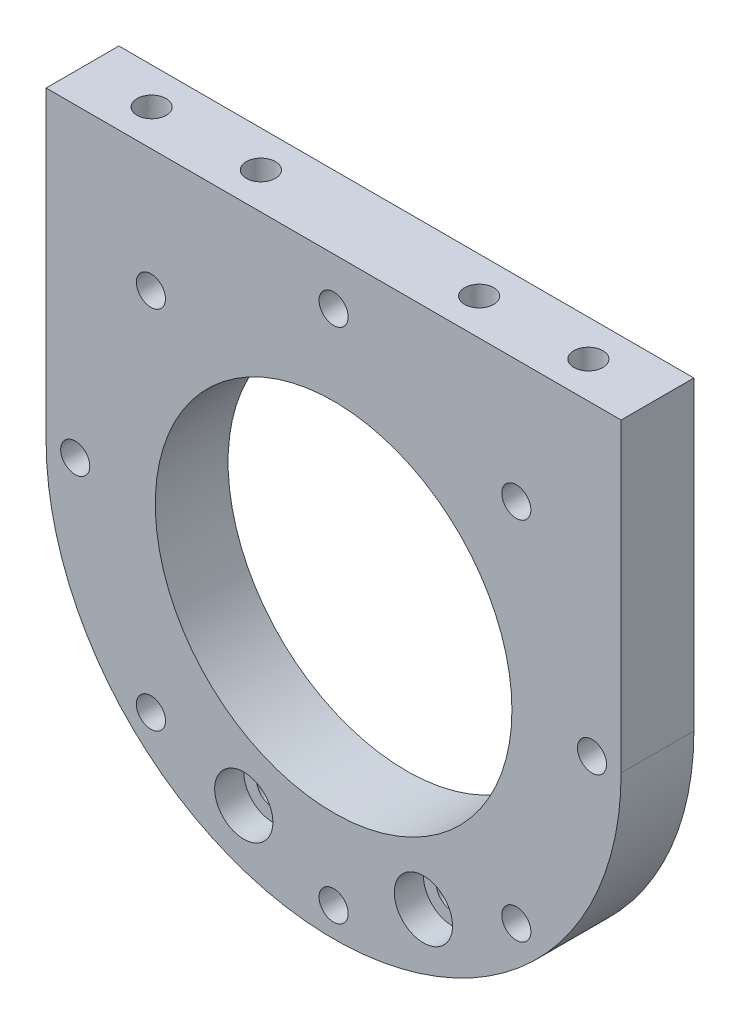
SolidWorks part; units mm, degrees
material "1060 합금"
ref_plane "정면" through (0, 0, 0) normal (0, 0, 1) x (1, 0, 0)
ref_plane "윗면" through (0, 0, 0) normal (0, 1, 0) x (1, 0, 0)
ref_plane "우측면" through (0, 0, 0) normal (1, 0, 0) x (0, 0, -1)
sketch "스케치1" plane through (0, 0, 0) normal (0, 0, 1) x (1, 0, 0)
  line L0 (0, 0) -> (0, 56.4093) construction
  line L1 (-39.5, 0) -> (-39.5, 42)
  line L2 (-39.5, 42) -> (39.5, 42)
  line L3 (39.5, 42) -> (39.5, 0)
  line L4 (0, 0) -> (0, -35.5) construction
  line L5 (0, 0) -> (-12.3415, -29.7951) construction
  line L6 (0, 0) -> (12.3415, -29.7951) construction
  arc A0 (-39.5, 0) -> (39.5, 0) centre (0, 0) ccw
  circle A1 centre (0, 0) radius 35.5 construction
  circle A2 centre (0, -35.5) radius 2
  circle A3 centre (-25.1023, -25.1023) radius 2
  circle A4 centre (-35.5, 0) radius 2
  circle A5 centre (-25.1023, 25.1023) radius 2
  circle A6 centre (0, 35.5) radius 2
  circle A7 centre (25.1023, 25.1023) radius 2
  circle A8 centre (35.5, 0) radius 2
  circle A9 centre (25.1023, -25.1023) radius 2
  circle A10 centre (0, 0) radius 24.5
  circle A11 centre (0, 0) radius 32.25 construction
  circle A12 centre (-12.3415, -29.7951) radius 2.25
  circle A13 centre (12.3415, -29.7951) radius 2.25
  point P27 (0, 0)
  dimension "D1" = 79
  dimension "D2" = 71
  dimension "D3" = 4
  dimension "D4" = 49
  dimension "D7" = 22.5
  dimension "D9" = 4.5
  dimension "D10" = 4.5
  dimension "D5" = 42
  dimension "D8" = 22.5
  dimension "D6" = 8
extrude "보스-돌출1" add sketch "스케치1" along normal blind 10
sketch "스케치2" plane through (0, 42, 0) normal (0, 1, 0) x (1, 0, 0)
  line L0 (-39.5, -5) -> (39.5, -5) construction
  line L1 (-39.5, -10) -> (-39.5, 0) construction
  line L2 (39.5, -10) -> (39.5, 0) construction
  circle A0 centre (-30, -5) radius 2
  circle A1 centre (-15, -5) radius 2
  circle A2 centre (15, -5) radius 2
  circle A3 centre (30, -5) radius 2
  dimension "D1" = 4
  dimension "D2" = 4
  dimension "D3" = 4
  dimension "D4" = 4
  dimension "D5" = 15
  dimension "D6" = 15
  dimension "D7" = 15
  dimension "D8" = 15
extrude "컷-돌출1" cut sketch "스케치2" against normal blind 15
sketch "스케치4" plane through (0, 0, 10) normal (0, 0, 1) x (1, 0, 0)
  circle A0 centre (-12.3415, -29.7951) radius 4
  circle A1 centre (12.3415, -29.7951) radius 4
  dimension "D1" = 8
  dimension "D2" = 8
extrude "컷-돌출3" cut sketch "스케치4" against normal blind 4
